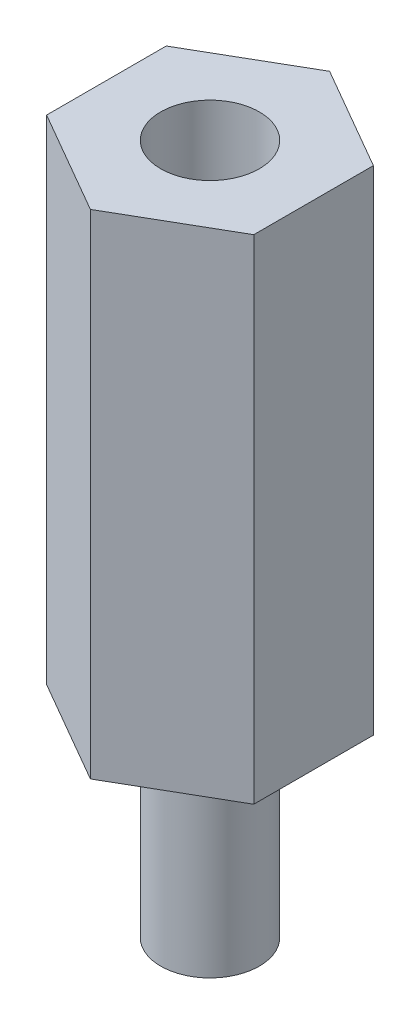
SolidWorks part; units mm, degrees
ref_plane "Front Plane" through (0, 0, 0) normal (0, 0, 1) x (1, 0, 0)
ref_plane "Top Plane" through (0, 0, 0) normal (0, 1, 0) x (1, 0, 0)
ref_plane "Right Plane" through (0, 0, 0) normal (1, 0, 0) x (0, 0, -1)
sketch "Sketch1" plane through (0, 0, 0) normal (0, 1, 0) x (1, 0, 0)
  line L1 (0, 3.6373) -> (-3.15, 1.8187)
  line L2 (-3.15, 1.8187) -> (-3.15, -1.8187)
  line L3 (-3.15, -1.8187) -> (0, -3.6373)
  line L4 (0, -3.6373) -> (3.15, -1.8187)
  line L5 (3.15, -1.8187) -> (3.15, 1.8187)
  line L6 (3.15, 1.8187) -> (0, 3.6373)
  circle A0 centre (0, 0) radius 3.15 construction
extrude "Boss-Extrude1" add sketch "Sketch1" along normal blind 15
sketch "Sketch2" plane through (0, 0, 0) normal (0, -1, 0) x (1, 0, 0)
  circle A0 centre (0, 0) radius 1.5
extrude "Boss-Extrude2" add sketch "Sketch2" along normal blind 6
sketch "Sketch3" plane through (0, 15, 0) normal (0, 1, 0) x (1, 0, 0)
  circle A0 centre (0, 0) radius 1.5
extrude "Cut-Extrude1" cut sketch "Sketch3" against normal blind 3
